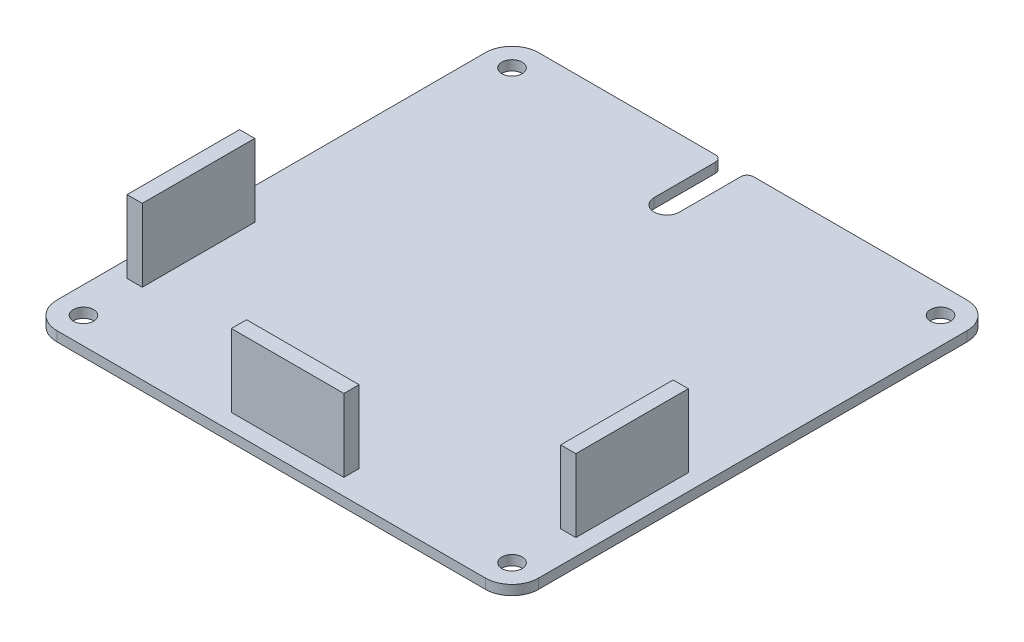
SolidWorks part; units mm, degrees
ref_plane "Front Plane" through (0, 0, 0) normal (0, 0, 1) x (1, 0, 0)
ref_plane "Top Plane" through (0, 0, 0) normal (0, 1, 0) x (1, 0, 0)
ref_plane "Right Plane" through (0, 0, 0) normal (1, 0, 0) x (0, 0, -1)
sketch "Base plate" plane through (0, 0, 0) normal (0, 1, 0) x (1, 0, 0)
  line L0 (-2.9, 38.1) -> (-2.9, 27.4) construction
  line L1 (-33.9, -38.1) -> (33.9, -38.1)
  line L2 (-38.1, -33.9) -> (-38.1, 33.9)
  line L3 (-33.9, 38.1) -> (33.9, 38.1)
  line L4 (38.1, -33.9) -> (38.1, 33.9)
  line L5 (-38.1, -38.1) -> (38.1, 38.1) construction
  line L6 (-38.1, 38.1) -> (38.1, -38.1) construction
  line L7 (-0.9, 38.1) -> (-0.9, 27.4)
  line L8 (-4.9, 38.1) -> (-4.9, 27.4)
  circle A0 centre (-33.9, 33.9) radius 1.6
  circle A1 centre (33.9, 33.9) radius 1.6
  circle A2 centre (33.9, -33.9) radius 1.6
  circle A3 centre (-33.9, -33.9) radius 1.6
  arc A4 (-33.9, -38.1) -> (-38.1, -33.9) centre (-33.9, -33.9) cw
  arc A5 (33.9, -38.1) -> (38.1, -33.9) centre (33.9, -33.9) ccw
  arc A6 (33.9, 38.1) -> (38.1, 33.9) centre (33.9, 33.9) cw
  arc A7 (-38.1, 33.9) -> (-33.9, 38.1) centre (-33.9, 33.9) cw
  arc A9 (-4.9, 27.4) -> (-0.9, 27.4) centre (-2.9, 27.4) ccw
  point P0 (0, 0)
  dimension "D2" = 3.2
  dimension "D4" = 4.2
  dimension "D5" = 2
  dimension "D6" = 12.7
  dimension "D1" = 76.2
  dimension "D3" = 4.2
  dimension "D7" = 39
extrude "PCB" add sketch "Base plate" along normal blind 1.55 contours A9 L8 L3 A7 L2 A4 L1 A5 L4 A6 L7 A3 A2 A1 A0
fillet "圆角1" radius 1 2 edges at (-0.9, 0.775, -38.1) (-4.9, 0.775, -38.1)
sketch "草图2" plane through (0, 1.55, 0) normal (0, 1, 0) x (1, 0, 0)
  line L1 (-35.5, -7.6) -> (-33.1, -7.6)
  line L2 (-35.5, -7.6) -> (-35.5, -25.4)
  line L3 (-35.5, -25.4) -> (-33.1, -25.4)
  line L4 (-33.1, -7.6) -> (-33.1, -25.4)
  line L5 (35.5, -7.6) -> (33.1, -7.6)
  line L6 (35.5, -7.6) -> (35.5, -25.4)
  line L7 (35.5, -25.4) -> (33.1, -25.4)
  line L8 (33.1, -7.6) -> (33.1, -25.4)
  line L9 (-8.9, -33.1) -> (8.9, -33.1)
  line L10 (-8.9, -33.1) -> (-8.9, -35.5)
  line L11 (-8.9, -35.5) -> (8.9, -35.5)
  line L12 (8.9, -33.1) -> (8.9, -35.5)
  line L13 (-33.9, -38.1) -> (33.9, -38.1) construction
  line L15 (0, 0) -> (0, -35.5) construction
  line L16 (-38.1, -33.9) -> (-38.1, 33.9) construction
  line L17 (-33.1, -16.5) -> (33.1, -16.5) construction
  point P14 (0, -33.1)
  dimension "D1" = 2.6
  dimension "D2" = 17.8
  dimension "D3" = 12.7
  dimension "D4" = 2.4
  dimension "D5" = 2.6
extrude "Lidar pins" add sketch "草图2" along normal blind 8.5
sketch "草图3" plane through (0, 10.05, 0) normal (0, 1, 0) x (1, 0, 0)
  line L1 (-33.1, -7.6) -> (-35.5, -7.6)
  line L2 (-33.1, -7.6) -> (-33.1, -25.4)
  line L3 (-33.1, -25.4) -> (-35.5, -25.4)
  line L4 (-35.5, -7.6) -> (-35.5, -25.4)
  line L5 (8.9, -33.1) -> (-8.9, -33.1)
  line L6 (8.9, -33.1) -> (8.9, -35.5)
  line L7 (8.9, -35.5) -> (-8.9, -35.5)
  line L8 (-8.9, -33.1) -> (-8.9, -35.5)
  line L9 (35.5, -7.6) -> (33.1, -7.6)
  line L10 (35.5, -7.6) -> (35.5, -25.4)
  line L11 (35.5, -25.4) -> (33.1, -25.4)
  line L12 (33.1, -7.6) -> (33.1, -25.4)
extrude "Lidar pin headers" add sketch "草图3" along normal offset from surface (3 mm away) 11.5 up to face at (-1.2429, 1.55, -14.5439) offset beyond the face yes
